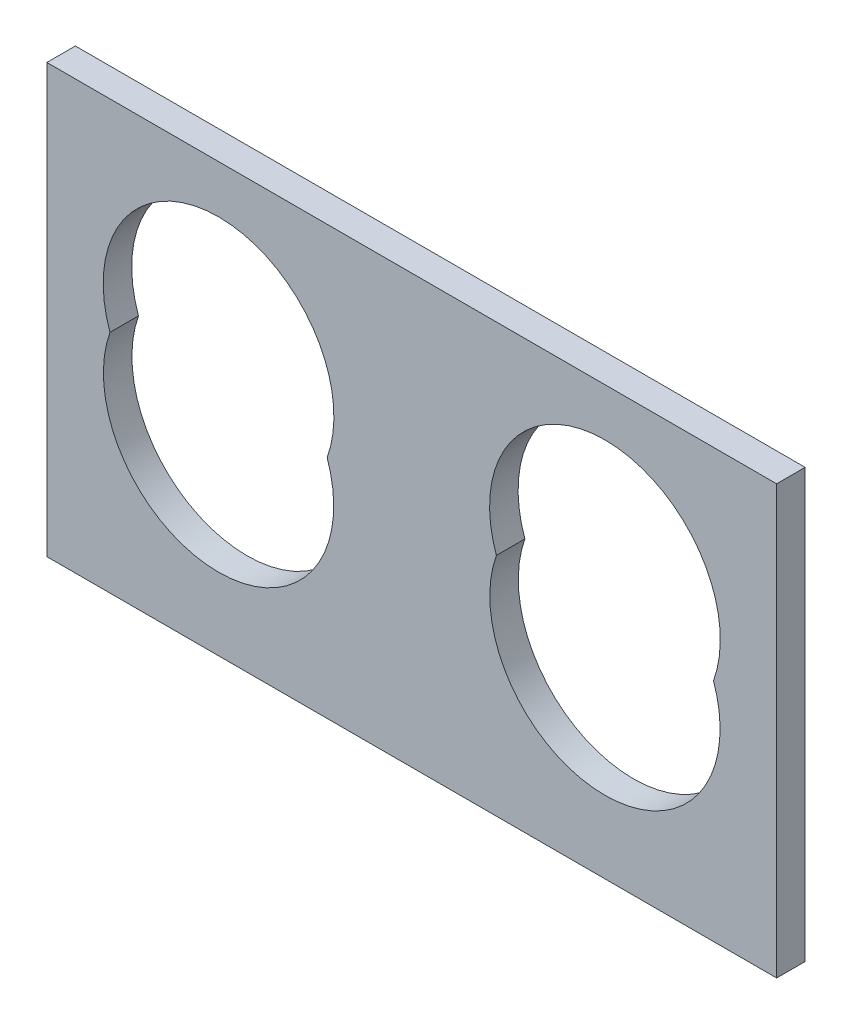
SolidWorks part; units mm, degrees
ref_plane "Front Plane" through (0, 0, 0) normal (0, 0, 1) x (1, 0, 0)
ref_plane "Top Plane" through (0, 0, 0) normal (0, 1, 0) x (1, 0, 0)
ref_plane "Right Plane" through (0, 0, 0) normal (1, 0, 0) x (0, 0, -1)
sketch "Sketch1" plane through (0, 0, 0) normal (0, 0, 1) x (1, 0, 0)
  line L0 (-27, 37) -> (18, 37) construction
  line L1 (-34.62, -30.465) -> (93.4045, -30.465)
  line L2 (-34.62, -30.465) -> (-34.62, 44.62)
  line L3 (-34.62, 44.62) -> (93.4045, 44.62)
  line L4 (93.4045, -30.465) -> (93.4045, 44.62)
  line L6 (18, -22.845) -> (-27, -22.845) construction
  line L7 (29.3923, 47.4436) -> (29.3923, -48.0943) construction
  line L8 (-1.522, 35.265) -> (0.428, 34.861) construction
  line L9 (-22.495, 23.506) -> (-23.167, 21.631) construction
  line L10 (14.167, 21.631) -> (14.645, 19.697) construction
  line L11 (-20.427, -8.82) -> (-22.01, -6.152) construction
  line L12 (13.01, -6.152) -> (11.427, -8.82) construction
  line L13 (-7.593, -16.823) -> (-4.5, -17.07) construction
  circle A0 centre (-4.5, 15.9942) radius 19.4742
  circle A1 centre (63.2846, 15.9942) radius 19.4742
  circle A2 centre (-4.5, 2.4297) radius 19.4378
  circle A3 centre (63.2845, 2.4297) radius 19.4378
  circle A4 centre (-4.5, 15.9942) radius 20.2362
  circle A5 centre (-4.5, 2.4297) radius 20.1998
  circle A6 centre (63.2845, 2.4297) radius 20.1998
  circle A7 centre (63.2846, 15.9942) radius 20.2362
  dimension "D5" = 0.762
  dimension "D6" = 0.762
  dimension "D1" = 7.62
  dimension "D2" = 7.62
  dimension "D3" = 7.62
  dimension "D4" = 7.62
extrude "Boss-Extrude1" add sketch "Sketch1" along normal blind 5 contours L3 L7 L1 L4 A7 A6 | L7 L3 L2 L1 A5 A4
